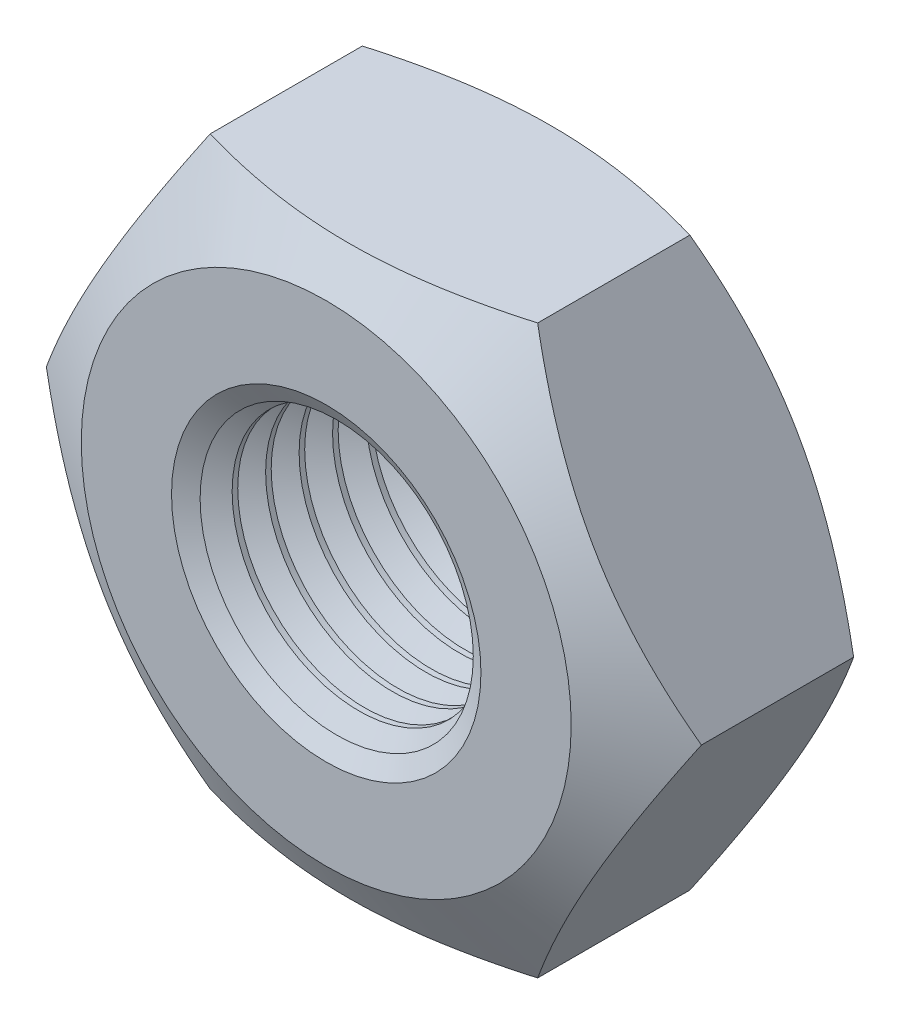
SolidWorks part; units mm, degrees
ref_plane "Front" through (0, 0, 0) normal (0, 0, 1) x (1, 0, 0)
ref_plane "Top" through (0, 0, 0) normal (0, 1, 0) x (1, 0, 0)
ref_plane "Right" through (0, 0, 0) normal (1, 0, 0) x (0, 0, -1)
sketch "Sketch1" plane through (0, 0, 0) normal (0, 0, 1) x (1, 0, 0)
  line L1 (3.1754, 0) -> (1.5877, 2.75)
  line L2 (1.5877, 2.75) -> (-1.5877, 2.75)
  line L3 (-1.5877, 2.75) -> (-3.1754, 0)
  line L4 (-3.1754, 0) -> (-1.5877, -2.75)
  line L5 (-1.5877, -2.75) -> (1.5877, -2.75)
  line L6 (1.5877, -2.75) -> (3.1754, 0)
  circle A0 centre (0, 0) radius 2.75 construction
  circle A1 centre (0, 0) radius 1.2295
  dimension "D" = 2.459
  dimension "s" = 5.5
extrude "BaseNut" add sketch "Sketch1" against normal blind 2.4
cosmetic thread "ThreadCosmetic1" [suppressed] parameters "D"=3
sketch "Sketch2" plane through (0, 0, 0) normal (0, 1, 0) x (1, 0, 0)
  line L0 (-3.1754, 2.4) -> (-2.375, 2.4)
  line L2 (-2.375, 2.4) -> (-3.1754, 1.9379)
  line L3 (-3.1754, 1.9379) -> (-3.1754, 2.4)
  line L4 (0, 3.3759) -> (0, -9.8171) construction
  line L6 (-9.7712, 1.2) -> (9.8853, 1.2) construction
  line L7 (-3.1754, 0.4621) -> (-3.1754, 0)
  line L8 (-2.375, 0) -> (-3.1754, 0.4621)
  line L9 (-3.1754, 0) -> (-2.375, 0)
  dimension "dw" = 4.75
  dimension "D1" = 30
  dimension "D2" = 1.2
revolve "Double-Chamfer" cut sketch "Sketch2" angle 360 about L4
chamfer "EndChamfer" distance 0.2705 angle 30 2 edges at (1.2295, 0, -2.4) (1.2295, 0, 0)
sketch "Sketch3" plane through (0, 0, 0) normal (0, 1, 0) x (1, 0, 0)
  line L0 (-1.4638, 2.1295) -> (-1.2295, 1.9942)
  line L1 (-1.2295, 1.9942) -> (-0.959, 1.9942)
  line L2 (-0.959, 1.9942) -> (-0.959, 2.2647)
  line L3 (-0.959, 2.2647) -> (-1.2295, 2.2647)
  line L4 (-1.2295, 2.2647) -> (-1.4638, 2.1295)
  line L5 (0, 7.4383) -> (0, 16.8806) construction
  dimension "D1" = 0.2705
  dimension "D2" = 2.459
revolve "Cut-Revolve10" cut sketch "Sketch3" angle 360 about L5
pattern_linear "LPattern10" count 7 spacing 0.3246 along (0, 0, 1) of "Cut-Revolve10"
equation "\"dw@Sketch2\" = \"s@Sketch1\"-0.75"
equation "\"D2@Sketch2\" = \"m@BaseNut\" / 2"
equation "\"D2@Sketch3\" = \"D@Sketch1\""
equation "\"D1@Sketch3\" =  (\"D@ThreadCosmetic1\"   - \"D@Sketch1\")  / 2"
equation "\"D3@LPattern10\" = \"D1@Sketch3\" * 1.2"
equation "\"D1@LPattern10\" = \"m@BaseNut\"/\"D3@LPattern10\""
